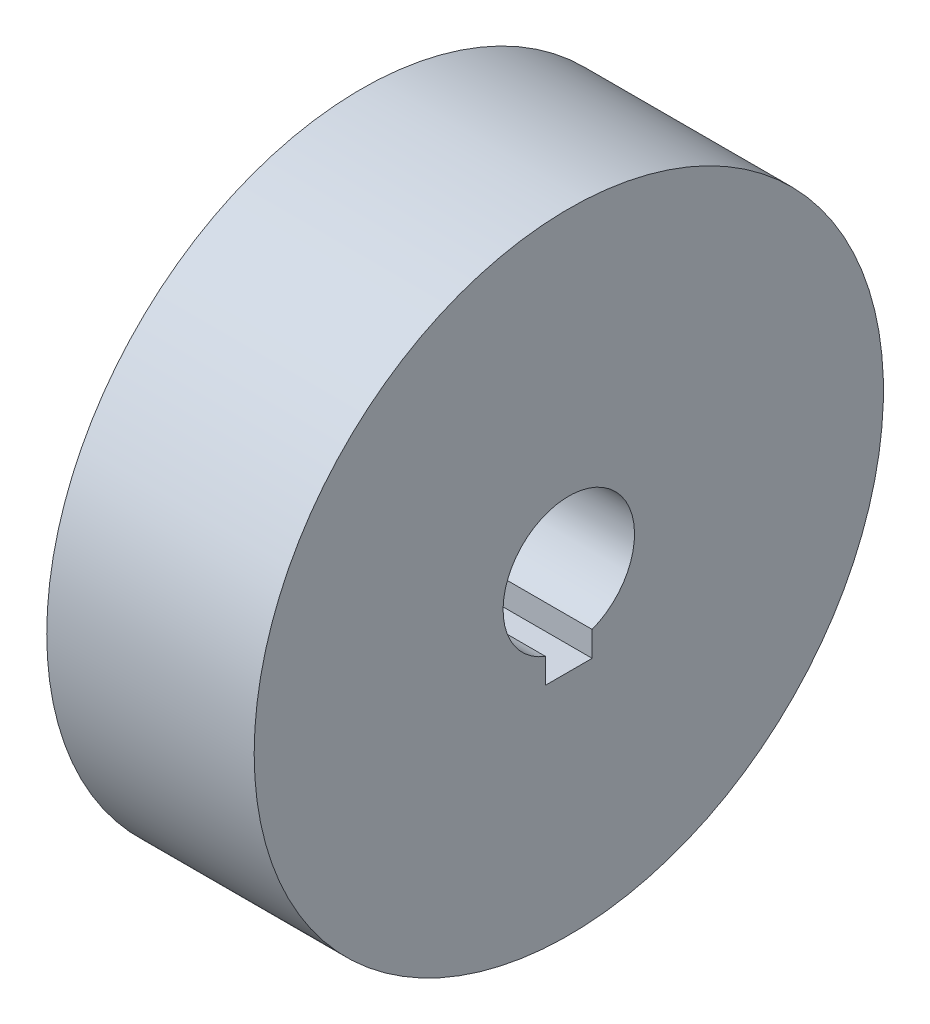
SolidWorks part; units mm, degrees
ref_plane "Front Plane" through (0, 0, 0) normal (0, 0, 1) x (1, 0, 0)
ref_plane "Top Plane" through (0, 0, 0) normal (0, 1, 0) x (1, 0, 0)
ref_plane "Right Plane" through (0, 0, 0) normal (1, 0, 0) x (0, 0, -1)
sketch "Sketch1" plane through (0, 0, 0) normal (0, 0, 1) x (1, 0, 0)
  line L2 (-35, 10) -> (0, 10)
  line L3 (0, 10) -> (0, 30)
  line L4 (0, 30) -> (-15, 30)
  line L5 (-35, 30) -> (-35, 10)
  line L6 (-20, 30) -> (-20, 40)
  line L7 (-15, 30) -> (-15, 40)
  line L8 (-20, 40) -> (-35, 40)
  line L9 (-15, 40) -> (0, 40)
  line L10 (-35, 45) -> (0, 45)
  line L12 (0, -36.8844) -> (0, 45)
  line L13 (-35, 45) -> (-35, -39.6573)
  line L14 (-20, 30) -> (-35, 30)
  line L15 (-20, -40) -> (-35, -40)
  line L16 (-35, -45) -> (-35, 39.6573)
  line L17 (-35, -45) -> (0, -45)
  line L18 (-15, -40) -> (0, -40)
  line L19 (0, -45) -> (0, 36.8844)
  line L20 (-20, -30) -> (-20, -40)
  line L21 (-15, -30) -> (-15, -40)
  line L22 (0, -30) -> (-15, -30)
  line L23 (-20, -30) -> (-35, -30)
  line L24 (-35, -10) -> (0, -10)
  line L26 (-102.9447, -57.9202) -> (90.9358, -57.9202) construction
  point P21 (-20, 35)
  point P22 (-15, 35)
  point P36 (-7.5, 40)
  point P37 (-17.5, 45)
  dimension "D1" = 80
  dimension "D3" = 5
  dimension "D4" = 20
  dimension "D6" = 80
  dimension "D7" = 90
revolve "Revolve-Thin1" add sketch "Sketch1" angle 360 about L26
sketch "Sketch2" plane through (-35, 0, 0) normal (-1, 0, 0) x (0, 0, 1)
  line L1 (-2.8119, -63.3401) -> (2.8119, -63.3401)
  line L2 (-2.8119, -63.3401) -> (-2.8119, -68.3407)
  line L3 (-2.8119, -68.3407) -> (2.8119, -68.3407)
  line L4 (2.8119, -63.3401) -> (2.8119, -68.3407)
  line L5 (-2.8119, -63.3401) -> (2.8119, -68.3407) construction
  line L6 (-2.8119, -68.3407) -> (2.8119, -63.3401) construction
  circle A0 centre (0, -57.9202) radius 7.9202 construction
  point P0 (0, -65.8404)
extrude "Cut-Extrude1" cut sketch "Sketch2" against normal blind 50
